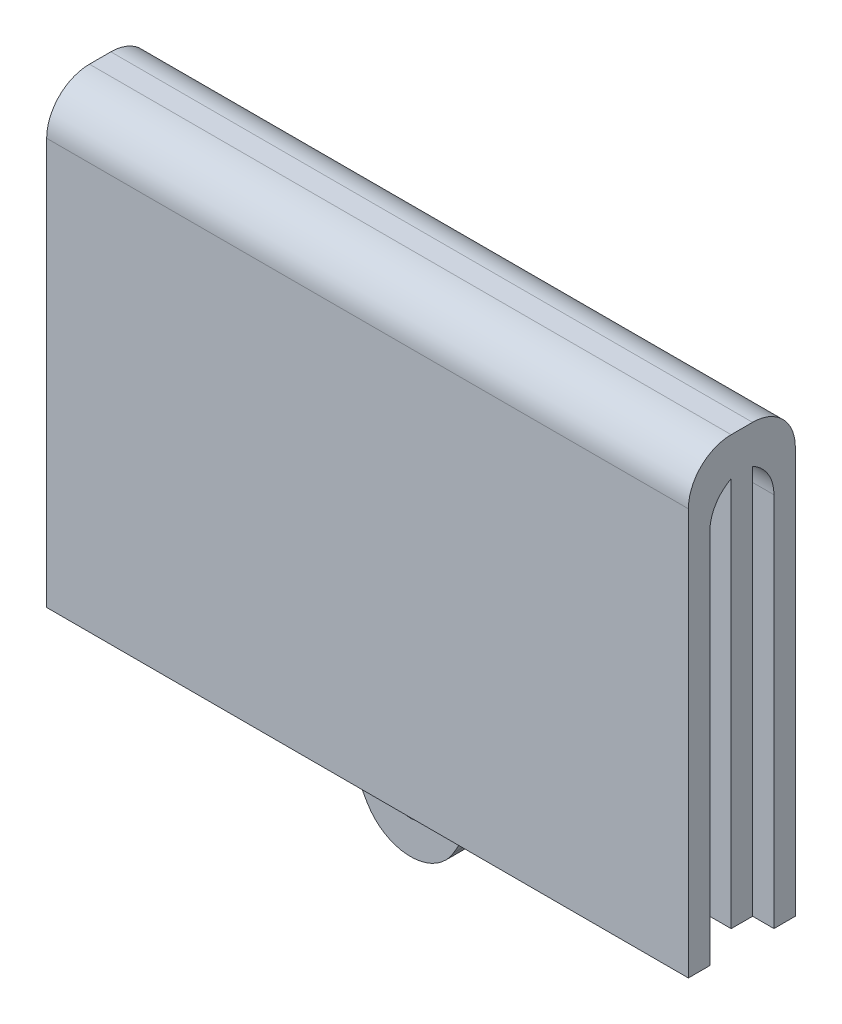
SolidWorks part; units mm, degrees
ref_plane "Front Plane" through (0, 0, 0) normal (0, 0, 1) x (1, 0, 0)
ref_plane "Top Plane" through (0, 0, 0) normal (0, 1, 0) x (1, 0, 0)
ref_plane "Right Plane" through (0, 0, 0) normal (1, 0, 0) x (0, 0, -1)
other "Configuration Table"
sketch "草图1" plane through (0, 0, 0) normal (0, 1, 0) x (1, 0, 0)
  line L1 (-30, -1) -> (30, -1)
  line L2 (-30, -1) -> (-30, 1)
  line L3 (-30, 1) -> (30, 1)
  line L4 (30, -1) -> (30, 1)
  line L5 (-30, -1) -> (30, 1) construction
  line L6 (-30, 1) -> (30, -1) construction
  point P0 (0, 0)
  dimension "D1" = 2
  dimension "D2" = 60
extrude "凸台-拉伸1" add sketch "草图1" along normal blind 40
sketch "草图3" plane through (0, 0, -1) normal (0, 0, -1) x (-1, 0, 0)
  line L0 (-4.0554, -6.8232) -> (-7.9948, 0)
  line L1 (-30, 0) -> (30, 0) construction
  line L2 (4.0217, -6.8232) -> (7.9611, 0)
  arc A0 (-4.0554, -6.8232) -> (4.0217, -6.8232) centre (-0.0168, -4.4916) ccw
  circle A1 centre (-0.0168, -4.4916) radius 1.55
  line M5 (-30, 0) -> (30, 0)
  dimension "D3" = 3.1
  dimension "D1" = 60
  dimension "D2" = 60
extrude "凸台-拉伸2" add sketch "草图3" against normal through all separate body contours L0 A0 L2 A1 M5
sketch "草图4" plane through (30, 0, 0) normal (1, 0, 0) x (0, 0, -1)
  line L4 (-1, 0) -> (1, 0)
  line L5 (1, 0) -> (1, 40)
  line L6 (1, 40) -> (-1, 40)
  line L7 (-1, 40) -> (-1, 0)
  line L10 (1, 40) -> (-1, 40) construction
  line L12 (0, 46.4254) -> (0, 13.5746) construction
  line L13 (5, 36) -> (5, -1.9934)
  line L17 (3, 33.1344) -> (3, -1.9934)
  line L18 (3, -1.9934) -> (5, -1.9934)
  line L21 (1, 40) -> (1, 36.4381)
  line L22 (1, 40) -> (1, 0) construction
  line L30 (-5, 36) -> (-5, -1.9934)
  line L31 (-3, -1.9934) -> (-5, -1.9934)
  line L32 (-3, 33.1344) -> (-3, -1.9934)
  line L34 (-1, 40) -> (-1, 36.4381)
  arc A0 (1, 40) -> (5, 36) centre (1, 36) cw
  arc A2 (3, 33.1344) -> (1, 36.4381) centre (-0.7286, 33.1344) ccw
  arc A4 (-1, 40) -> (-5, 36) centre (-1, 36) ccw
  arc A5 (-3, 33.1344) -> (-1, 36.4381) centre (0.7286, 33.1344) cw
  point P13 (0, 40)
  dimension "D2" = 5
  dimension "D3" = 2
  dimension "D1" = 0
extrude "凸台-拉伸3" add sketch "草图4" against normal through all
